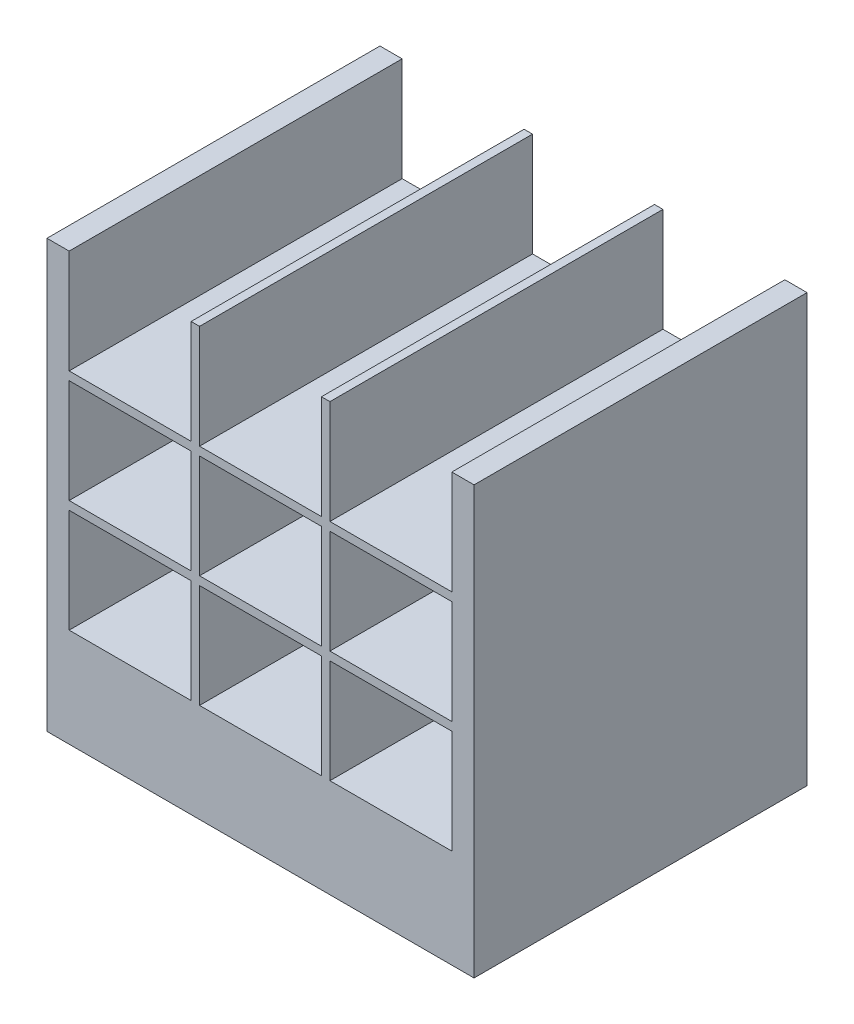
SolidWorks part; units mm, degrees
material "Nylon 101"
ref_plane "Front" through (0, 0, 0) normal (0, 0, 1) x (1, 0, 0)
ref_plane "Top" through (0, 0, 0) normal (0, 1, 0) x (1, 0, 0)
ref_plane "Right" through (0, 0, 0) normal (1, 0, 0) x (0, 0, -1)
sketch "Sketch1" plane through (0, 0, 0) normal (0, 0, 1) x (1, 0, 0)
  line L0 (90.9712, -69.2946) -> (90.9712, 388.6738) construction
  line L1 (412.1458, -77.4272) -> (412.1458, 403.4142) construction
  line L2 (0, 0) -> (480.95, 0)
  line L3 (0, 0) -> (0, 369.6812)
  line L4 (0, 369.6812) -> (480.95, 369.6812)
  line L5 (480.95, 0) -> (480.95, 369.6812)
  line L6 (25, 223.2992) -> (162.3, 223.2992) construction
  line L7 (162.3, 223.2992) -> (171.825, 223.2992) construction
  line L8 (171.825, 223.2992) -> (309.125, 223.2992) construction
  line L9 (25, 223.2992) -> (0, 223.2992) construction
  line L10 (455.95, 223.2992) -> (480.95, 223.2992) construction
  line L11 (93.65, 223.2992) -> (93.65, 195.0157) construction
  line L12 (309.125, 223.2992) -> (318.65, 223.2992) construction
  line L13 (318.65, 223.2992) -> (455.95, 223.2992) construction
  line L14 (129.2016, 0) -> (129.2016, 116.8771) construction
  line L15 (129.2016, 116.8771) -> (129.2016, 126.4021) construction
  line L16 (129.2016, 126.4021) -> (129.2016, 243.2791) construction
  line L17 (129.2016, 243.2791) -> (129.2016, 252.8041) construction
  line L18 (129.2016, 252.8041) -> (129.2016, 369.6812) construction
  line L19 (25, 369.6812) -> (25, 0)
  line L20 (455.95, 369.6812) -> (455.95, 0)
  line L21 (25, 252.8041) -> (455.95, 252.8041)
  line L22 (25, 243.2791) -> (455.95, 243.2791)
  line L23 (25, 126.4021) -> (455.95, 126.4021)
  line L24 (25, 116.8771) -> (455.95, 116.8771)
  line L25 (171.825, 369.6812) -> (171.825, 0)
  line L26 (162.3, 369.6812) -> (162.3, 0)
  line L27 (309.125, 369.6812) -> (309.125, 0)
  line L28 (318.65, 369.6812) -> (318.65, 0)
  line L30 (0, 0) -> (480.95, 0)
  line L31 (0, 0) -> (0, -111.2688)
  line L32 (0, -111.2688) -> (480.95, -111.2688)
  line L33 (480.95, 0) -> (480.95, -111.2688)
  dimension "D1" = 90.9712
  dimension "D2" = 68.8042
  dimension "D3" = 480.95
  dimension "D4" = 369.6812
  dimension "D5" = 25
  dimension "D6" = 9.525
  dimension "D7" = 480.95
extrude "Boss-Extrude1" add sketch "Sketch1" along normal blind 375 contours L19 L4 L3 L2 | L26 L21 L19 L22 | L21 L26 L22 L25 | L4 L26 L21 L25 | L22 L26 L23 L25 | L26 L23 L19 L24 | L23 L26 L24 L25 | L24 L26 L2 L25 | L27 L23 L25 L24 | L27 L21 L25 L22 | L28 L4 L27 L21 | L28 L21 L27 L22 | L28 L22 L27 L23 | L21 L28 L22 L20 | L4 L20 L2 L5 | L23 L28 L24 L20 | L28 L23 L27 L24 | L28 L24 L27 L2 | L33 L2 L31 L32
